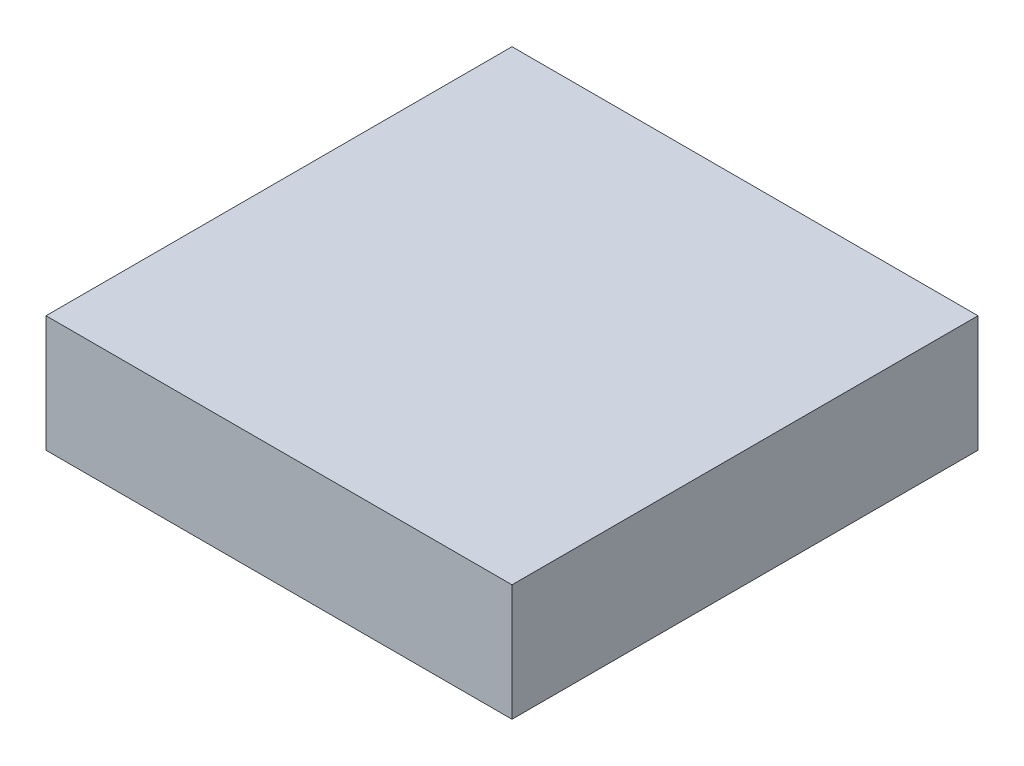
SolidWorks part; units mm, degrees
ref_plane "Front Plane" through (0, 0, 0) normal (0, 0, 1) x (1, 0, 0)
ref_plane "Top Plane" through (0, 0, 0) normal (0, 1, 0) x (1, 0, 0)
ref_plane "Right Plane" through (0, 0, 0) normal (1, 0, 0) x (0, 0, -1)
sketch "Sketch1" plane through (0, 0, 0) normal (0, 1, 0) x (1, 0, 0)
  line L1 (-1.5, -1.5) -> (1.5, -1.5)
  line L2 (-1.5, -1.5) -> (-1.5, 1.5)
  line L3 (-1.5, 1.5) -> (1.5, 1.5)
  line L4 (1.5, -1.5) -> (1.5, 1.5)
  line L5 (-1.5, -1.5) -> (1.5, 1.5) construction
  line L6 (-1.5, 1.5) -> (1.5, -1.5) construction
  point P0 (0, 0)
  dimension "D1" = 3
  dimension "D2" = 3
extrude "Boss-Extrude1" add sketch "Sketch1" along normal blind 0.75
sketch "Sketch2" plane through (0, 0, 0) normal (0, -1, 0) x (1, 0, 0)
  line L0 (-1.5, 1.5) -> (1.5, 1.5) construction
  line L2 (0.1, 1.5) -> (0.1, 1.223)
  line L3 (0.248, 1.075) -> (0.252, 1.075)
  line L4 (0.4, 1.5) -> (0.4, 1.223)
  line L5 (0.25, 1.5) -> (0.4, 1.075) construction
  line L6 (0.1, 1.075) -> (0.25, 1.5) construction
  line L7 (0, 0) -> (0, -1.7426) construction
  line L9 (0.6, 1.5) -> (0.6, 1.223)
  line L10 (0.748, 1.075) -> (0.752, 1.075)
  line L11 (0.9, 1.5) -> (0.9, 1.223)
  line L12 (0.75, 1.5) -> (0.9, 1.075) construction
  line L13 (0.6, 1.075) -> (0.75, 1.5) construction
  line L14 (-2.1683, 0) -> (2.9623, 0) construction
  line L20 (0.1, 1.5) -> (0.4, 1.5)
  line L21 (0.6, 1.5) -> (0.9, 1.5)
  line L22 (1.5, 1.5) -> (1.5, -1.5) construction
  line L27 (1.5, 0.9668) -> (1.075, 0.9668)
  line L28 (1.5, 0.9668) -> (1.5, 0.6668)
  line L29 (1.5, 0.6668) -> (1.075, 0.6668)
  line L30 (1.075, 0.9668) -> (1.075, 0.6668)
  line L32 (1.5, 0.533) -> (1.2058, 0.533)
  line L33 (1.5, 0.533) -> (1.5, 0.1924)
  line L34 (1.5, 0.1924) -> (1.2058, 0.1924)
  line L35 (1.2058, 0.533) -> (1.2058, 0.1924)
  arc A0 (0.252, 1.075) -> (0.4, 1.223) centre (0.252, 1.223) ccw
  arc A1 (0.1, 1.223) -> (0.248, 1.075) centre (0.248, 1.223) ccw
  arc A2 (0.752, 1.075) -> (0.9, 1.223) centre (0.752, 1.223) ccw
  arc A3 (0.748, 1.075) -> (0.6, 1.223) centre (0.748, 1.223) cw
  point P0 (0.25, 1.5)
  point P7 (0.75, 1.5)
  dimension "D1" = 0.148
  dimension "D2" = 0.148
  dimension "D3" = 0.25
  dimension "D4" = 0.5
  dimension "D5" = 0.425
  dimension "D6" = 0.3
